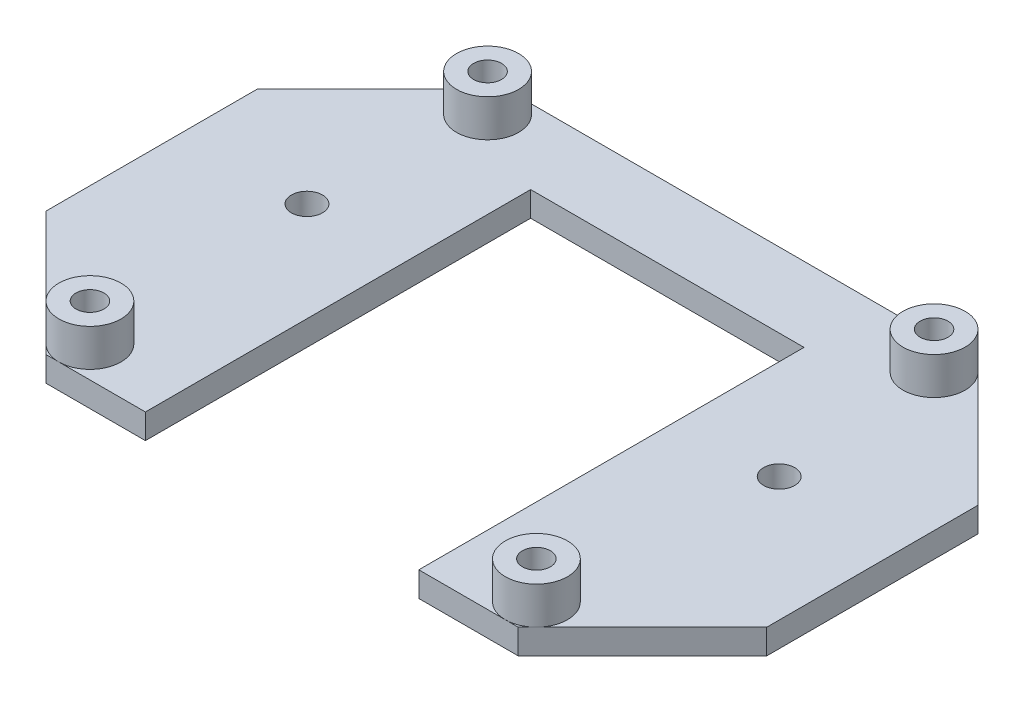
SolidWorks part; units mm, degrees
other "Camera1"
material "ABS"
ref_plane "Front" through (0, 0, 0) normal (0, 0, 1) x (1, 0, 0)
ref_plane "Top" through (0, 0, 0) normal (0, 1, 0) x (1, 0, 0)
ref_plane "Right" through (0, 0, 0) normal (1, 0, 0) x (0, 0, -1)
sketch "Sketch1" plane through (0, 0, 0) normal (0, 1, 0) x (1, 0, 0)
  line L1 (-58, -24) -> (58, -24)
  line L2 (-58, -24) -> (-58, 24)
  line L3 (-58, 24) -> (58, 24)
  line L4 (58, -24) -> (58, 24)
  line L5 (-58, -24) -> (58, 24) construction
  line L6 (-58, 24) -> (58, -24) construction
  point P0 (0, 0)
  dimension "D1" = 116
  dimension "D2" = 48
extrude "Boss-Extrude1" add sketch "Sketch1" along normal blind 4
sketch "Sketch2" plane through (0, 4, 0) normal (0, 1, 0) x (1, 0, 0)
  line L0 (-58, -24) -> (58, -24) construction
  line L5 (-58, 24) -> (-58, -24) construction
  line L6 (58, -24) -> (58, 24) construction
  circle A0 centre (-38, -2) radius 2.5
  circle A1 centre (38, -2) radius 2.5
  dimension "D1" = 5
  dimension "D2" = 5
  dimension "D3" = 20
  dimension "D4" = 20
  dimension "D5" = 22
extrude "Cut-Extrude1" cut sketch "Sketch2" against normal up to surface (4 mm away) up to face at (0, 0, 0)
sketch "Sketch3" plane through (0, 4, 0) normal (0, 1, 0) x (1, 0, 0)
  line L0 (-58, -24) -> (58, -24) construction
  line L1 (-22, -24) -> (22, -24)
  line L2 (-22, -24) -> (-22, 18)
  line L3 (-22, 18) -> (22, 18)
  line L4 (22, -24) -> (22, 18)
  point P6 (0, 18)
  dimension "D1" = 44
  dimension "D2" = 42
extrude "Cut-Extrude2" cut sketch "Sketch3" against normal up to surface (4 mm away) up to face at (-38, 0, -0.5)
sketch "Sketch4" plane through (0, 0, 24) normal (0, 0, 1) x (1, 0, 0)
  line L4 (-58, 0) -> (-22, 0)
  line L5 (-22, 0) -> (-22, 4)
  line L6 (-22, 4) -> (-58, 4)
  line L7 (-58, 4) -> (-58, 0)
  line L8 (-58, 0) -> (-22, 0)
  line L9 (-22, 0) -> (-22, 4)
  line L10 (-22, 4) -> (-58, 4)
  line L11 (-58, 4) -> (-58, 0)
  line L12 (58, 4) -> (22, 4)
  line L13 (22, 4) -> (22, 0)
  line L14 (22, 0) -> (58, 0)
  line L15 (58, 0) -> (58, 4)
  line L16 (58, 4) -> (22, 4)
  line L17 (22, 4) -> (22, 0)
  line L18 (22, 0) -> (58, 0)
  line L19 (58, 0) -> (58, 4)
  dimension "D1" = 0
  dimension "D2" = 0
extrude "Boss-Extrude2" add sketch "Sketch4" along normal blind 20
sketch "Sketch5" plane through (0, 0, -24) normal (0, 0, -1) x (-1, 0, 0)
  line L4 (-58, 0) -> (58, 0)
  line L5 (58, 0) -> (58, 4)
  line L6 (58, 4) -> (-58, 4)
  line L7 (-58, 4) -> (-58, 0)
  line L8 (-58, 0) -> (58, 0)
  line L9 (58, 0) -> (58, 4)
  line L10 (58, 4) -> (-58, 4)
  line L11 (-58, 4) -> (-58, 0)
  dimension "D1" = 0
extrude "Boss-Extrude3" add sketch "Sketch5" along normal blind 6
chamfer "Chamfer1" distance 20 angle 45 4 edges at (-58, 2, 44) (58, 2, 44) (58, 2, -30) (-58, 2, -30)
sketch "Sketch6" plane through (0, 4, 0) normal (0, 1, 0) x (1, 0, 0)
  line L0 (-38, 30) -> (38, 30) construction
  line L1 (-38, 30) -> (-58, 10) construction
  line L2 (58, 10) -> (38, 30) construction
  line L3 (38, -44) -> (58, -24) construction
  line L4 (38, -44) -> (22, -44) construction
  line L5 (-22, -44) -> (-38, -44) construction
  line L6 (-58, -24) -> (-38, -44) construction
  circle A0 centre (-35.9289, 25) radius 5
  circle A1 centre (35.9289, 25) radius 5
  circle A2 centre (35.9289, -39) radius 5
  circle A3 centre (-35.9289, -39) radius 5
  dimension "D1" = 10
  dimension "D2" = 10
  dimension "D3" = 10
  dimension "D4" = 10
extrude "Boss-Extrude4" add sketch "Sketch6" along normal blind 6
sketch "Sketch7" plane through (0, 10, 0) normal (0, 1, 0) x (1, 0, 0)
  circle A0 centre (-35.9289, 25) radius 2.25
  circle A1 centre (35.9289, 25) radius 2.25
  circle A2 centre (35.9289, -39) radius 2.25
  circle A3 centre (-35.9289, -39) radius 2.25
  dimension "D1" = 4.5
extrude "Cut-Extrude3" cut sketch "Sketch7" against normal up to surface (10 mm away) up to face at (0, 0, 9)
